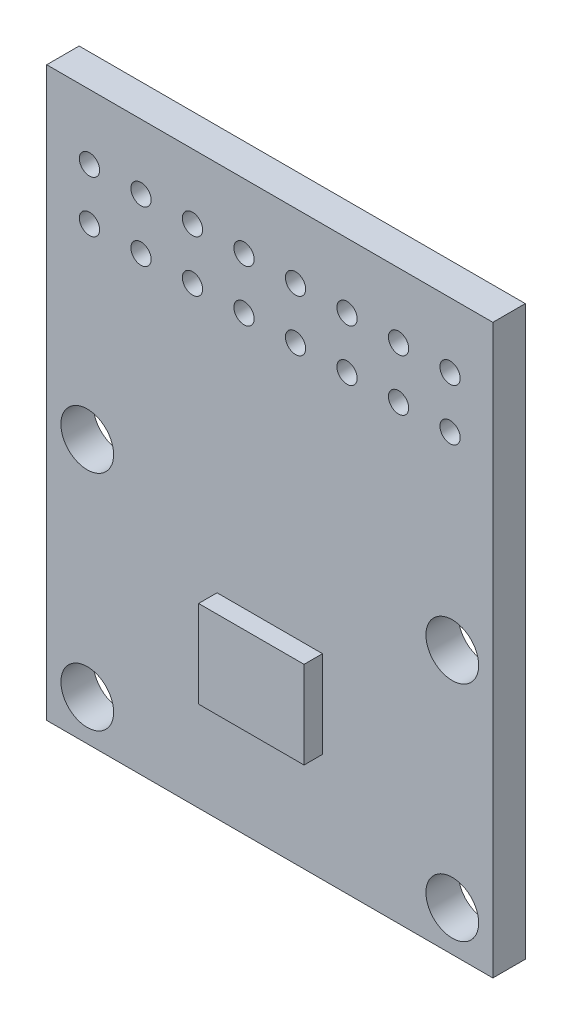
SolidWorks part; units mm, degrees
ref_plane "前视基准面" through (0, 0, 0) normal (0, 0, 1) x (1, 0, 0)
ref_plane "上视基准面" through (0, 0, 0) normal (0, 1, 0) x (1, 0, 0)
ref_plane "右视基准面" through (0, 0, 0) normal (1, 0, 0) x (0, 0, -1)
sketch "草图1" plane through (0, 0, 0) normal (0, 0, 1) x (1, 0, 0)
  line L0 (0, 5.0538) -> (0, -5.9862) construction
  line L1 (-11, -14) -> (11, -14)
  line L2 (-11, -14) -> (-11, 14)
  line L3 (-11, 14) -> (11, 14)
  line L4 (11, -14) -> (11, 14)
  line L5 (-11, -14) -> (11, 14) construction
  line L6 (-11, 14) -> (11, -14) construction
  line L7 (-1.27, 10.8) -> (1.27, 10.8) construction
  circle A0 centre (-9, -1) radius 1.3
  circle A1 centre (-9, -12) radius 1.3
  circle A2 centre (9, -12) radius 1.3
  circle A3 centre (9, -1) radius 1.3
  circle A4 centre (-8.89, 10.8) radius 0.5
  circle A5 centre (-6.35, 10.8) radius 0.5
  circle A6 centre (-3.81, 10.8) radius 0.5
  circle A7 centre (-1.27, 10.8) radius 0.5
  circle A8 centre (1.27, 10.8) radius 0.5
  circle A9 centre (3.81, 10.8) radius 0.5
  circle A10 centre (6.35, 10.8) radius 0.5
  circle A11 centre (8.89, 10.8) radius 0.5
  circle A12 centre (-6.35, 8.26) radius 0.5
  circle A13 centre (-3.81, 8.26) radius 0.5
  circle A14 centre (-1.27, 8.26) radius 0.5
  circle A15 centre (1.27, 8.26) radius 0.5
  circle A16 centre (3.81, 8.26) radius 0.5
  circle A17 centre (6.35, 8.26) radius 0.5
  circle A18 centre (8.89, 8.26) radius 0.5
  circle A19 centre (-8.89, 8.26) radius 0.5
  point P0 (0, 0)
  point P12 (0, 10.8)
  dimension "D3" = 2.6
  dimension "D4" = 11
  dimension "D5" = 9
  dimension "D6" = 2
  dimension "D7" = 2.6
  dimension "D8" = 1
  dimension "D9" = 3.2
  dimension "D13" = 2.54
  dimension "D1" = 22
  dimension "D2" = 28
  dimension "D12" = 2.54
  dimension "D10" = 8
  dimension "D11" = 2
extrude "凸台-拉伸1" add sketch "草图1" along normal blind 1.6
sketch "草图2" plane through (0, 0, 1.6) normal (0, 0, 1) x (1, 0, 0)
  line L0 (-9, -1) -> (9, -12) construction
  line L1 (-9, -12) -> (9, -1) construction
  line L3 (-2.6, -8.65) -> (2.6, -8.65)
  line L4 (-2.6, -8.65) -> (-2.6, -4.35)
  line L5 (-2.6, -4.35) -> (2.6, -4.35)
  line L6 (2.6, -8.65) -> (2.6, -4.35)
  line L7 (-2.6, -8.65) -> (2.6, -4.35) construction
  line L8 (-2.6, -4.35) -> (2.6, -8.65) construction
  point P8 (0, -6.5)
  dimension "D1" = 4.3
  dimension "D2" = 5.2
extrude "凸台-拉伸2" add sketch "草图2" along normal blind 0.91
